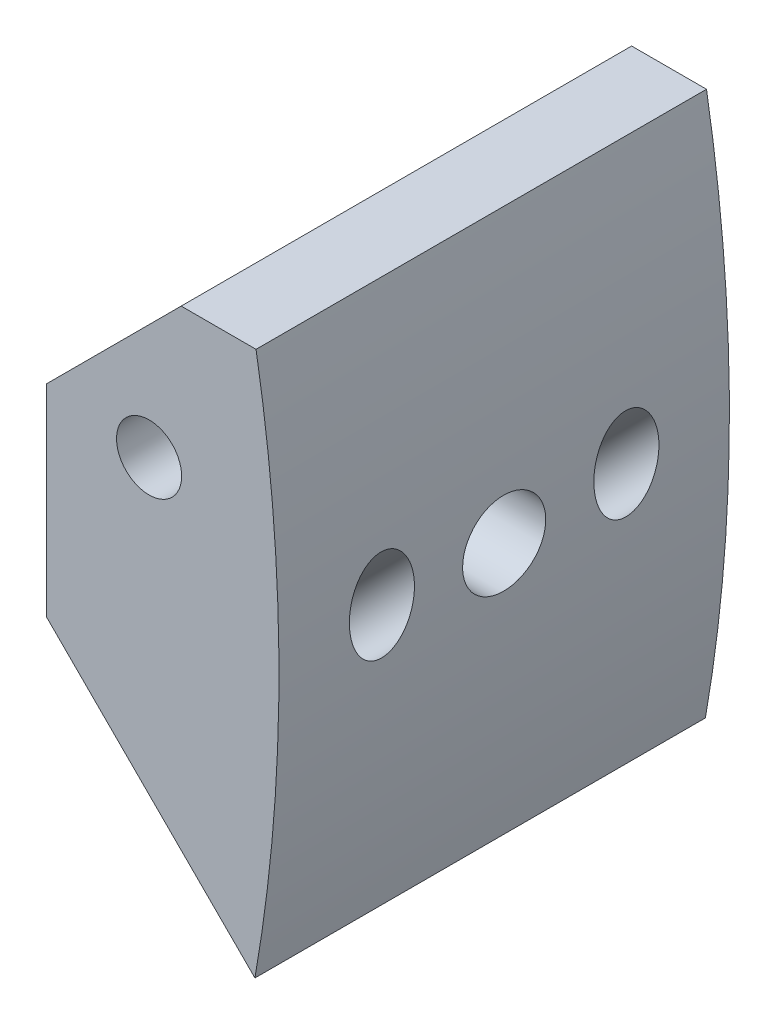
SolidWorks part; units mm, degrees
material "6061-T6 (SS)"
ref_plane "Front Plane" through (0, 0, 0) normal (0, 0, 1) x (1, 0, 0)
ref_plane "Top Plane" through (0, 0, 0) normal (0, 1, 0) x (1, 0, 0)
ref_plane "Right Plane" through (0, 0, 0) normal (1, 0, 0) x (0, 0, -1)
sketch "Sketch1" plane through (0, 0, 0) normal (0, 0, 1) x (1, 0, 0)
  line L0 (0, 0) -> (0, -13.1746)
  line L1 (0, -13.1746) -> (15.3242, -28.4988)
  line L2 (0, -6.5873) -> (15.3242, -6.5873) construction
  line L3 (15.3242, 15.3242) -> (0, 0) construction
  line L4 (15.3242, 15.3242) -> (15.3242, -6.5873) construction
  line L5 (15.3242, -6.5873) -> (15.3242, -28.4988) construction
  line L6 (19.05, -6.5873) -> (0, -6.5873) construction
  line L7 (0, 0) -> (0, 15.3242)
  line L8 (0, 15.3242) -> (15.3242, 15.3242)
  arc A0 (15.3242, 15.3242) -> (15.3242, -28.4988) centre (-47.244, -6.5873) cw
  dimension "D1" = 66.294
  dimension "D3" = 19.05
  dimension "D2" = 135
  dimension "D4" = 15.3242
extrude "Extrude1" add sketch "Sketch1" along normal blind 18.7198
sketch "Sketch23" plane through (0, 0, 0) normal (-1, 0, 0) x (0, 0, 1)
  line L0 (0, 0) -> (18.7198, 0) construction
  line L1 (18.7198, 15.3242) -> (18.7198, -13.1746) construction
  line L2 (9.3599, 0) -> (9.3599, -13.1746) construction
  line L3 (18.7198, -13.1746) -> (0, -13.1746) construction
  point P9 (9.3599, -6.5873)
sketch "Sketch2" plane through (0, 0, 0) normal (-1, 0, 0) x (0, 0, 1)
  line L0 (0, -6.5657) -> (18.7198, -6.5657) construction
  line L3 (9.3599, -13.1746) -> (9.3599, -6.5657) construction
  line L4 (18.7198, -13.1746) -> (0, -13.1746) construction
  point P6 (9.3599, -6.5657)
  dimension "D1" = 6.6089
sketch "Sketch13" plane through (0, 0, 18.7198) normal (0, 0, 1) x (1, 0, 0)
  line L0 (0, -13.1746) -> (0, 4.6054) construction
  line L1 (0, 4.6054) -> (30.3361, 4.6054)
  line L2 (0, 4.6054) -> (0, 31.0448)
  line L3 (0, 31.0448) -> (30.3361, 31.0448)
  line L4 (30.3361, 4.6054) -> (30.3361, 31.0448)
  dimension "D1" = 26.4394
  dimension "D2" = 30.3361
  dimension "D3" = 17.78
extrude "Extrude2" cut sketch "Sketch13" against normal through all
sketch "Sketch7" plane through (0, 0, 18.7198) normal (0, 0, 1) x (1, 0, 0)
  line L5 (19.05, -6.5873) -> (13.6525, -6.5873) construction
  line L6 (13.6525, -6.5873) -> (13.6525, -1.5073) construction
  arc A5 (15.3242, -28.4988) -> (18.0983, 4.6054) centre (-47.244, -6.5873) ccw construction
  dimension "D2" = 5.3975
  dimension "D4" = 5.08
hole_wizard "#6-32 Tapped Hole2" positions "Sketch9" profile "Sketch8" tap size "#6-32" standard "Ansi Inch" end condition through all
sketch "Sketch9" plane through (0, 0, 18.7198) normal (0, 0, 1) x (1, 0, 0)
  point P11 (13.6525, -1.5073)
sketch "Sketch8" plane through (13.6525, -1.5073, 18.7198) normal (1, 0, 0) x (0, -1, 0)
  line L0 (0, 0) -> (0, 18.7198)
  line L1 (0, 18.7198) -> (1.3525, 18.7198)
  line L2 (1.3525, 18.7198) -> (1.3525, 0)
  line L5 (1.3525, 0) -> (0, 0)
  line L11 (0, -6.35) -> (0, 107.95) construction
  dimension "Thread Major Dia." = 2.7051
  dimension "Thru Tap Drill Depth" = 18.7198
sketch "Sketch10" plane through (-6.5873, -6.5873, 0) normal (-0.7071, -0.7071, 0) x (0.7071, -0.7071, 0)
  line L0 (30.9875, 9.3599) -> (18.5415, 9.3599) construction
  line L2 (18.5415, 9.3599) -> (18.5415, 16.9799) construction
  line L3 (18.5415, 9.3599) -> (18.5415, 1.7399) construction
  line L5 (30.9875, 18.7198) -> (30.9875, 0) construction
  dimension "D1" = 7.62
  dimension "D2" = 12.446
sketch "Sketch14" plane through (0, 0, 18.7198) normal (0, 0, 1) x (1, 0, 0)
  line L0 (0.6847, -13.8593) -> (7.2762, -7.2678)
  line L1 (0, -13.1746) -> (15.3242, -28.4988) construction
  line L2 (7.2762, -7.2678) -> (18.0525, -18.0441)
  line L3 (21.9157, -21.9073) -> (15.3242, -28.4988)
  line L4 (15.3242, -28.4988) -> (0.6847, -13.8593)
  line L5 (18.0525, -18.0441) -> (21.9157, -21.9073)
  arc A0 (15.3242, -28.4988) -> (18.0983, 4.6054) centre (-47.244, -6.5873) ccw construction
  dimension "D2" = 9.3218
  dimension "D3" = 15.24
extrude "Extrude3" cut sketch "Sketch14" against normal through all
sketch "Sketch16" plane through (0.0042, 0.0042, 0) normal (-0.7071, -0.7071, 0) x (0, 0, 1)
  line L2 (9.3599, -17.8863) -> (14.4399, -17.8863) construction
  line L3 (9.3599, -17.8863) -> (4.2799, -17.8863) construction
  line L4 (9.3599, -25.5242) -> (9.3599, -17.8863) construction
  line L5 (18.7198, -25.5242) -> (0, -25.5242) construction
  dimension "D1" = 10.16
  dimension "D3" = 7.6379
hole_wizard "#6-32 Tapped Hole1" positions "3DSketch1" profile "Sketch17" tap size "#6-32" standard "Ansi Inch" end condition through all
sketch3d "3DSketch1"
  point P0 (12.6517, -12.6433, 14.4399)
  point P8 (12.6517, -12.6433, 4.2799)
sketch "Sketch17" plane through (12.6517, -12.6433, 14.4399) normal (0, 0, 1) x (0.7071, -0.7071, 0)
  line L0 (0, 0) -> (0, 16.7209)
  line L1 (0, 16.7209) -> (1.3525, 16.7209)
  line L2 (1.3525, 16.7209) -> (1.3525, 0)
  line L5 (1.3525, 0) -> (0, 0)
  line L11 (0, -6.35) -> (0, 107.95) construction
  dimension "Thread Major Dia." = 2.7051
  dimension "Thru Tap Drill Depth" = 16.7209
hole_wizard "#8-32 Tapped Hole1" positions "Sketch4" profile "Sketch5" tap size "#8-32" standard "Ansi Inch"
sketch "Sketch4" plane through (0, 0, 0) normal (-1, 0, 0) x (0, 0, 1)
  line L0 (0, -6.5657) -> (18.7198, -6.5657) construction
  point P1 (9.3599, -6.5657)
sketch "Sketch5" plane through (0, -6.5657, 9.3599) normal (0, 1, 0) x (0, 0, 1)
  line L0 (0, 0) -> (0, 19.05)
  line L1 (0, 19.05) -> (1.7272, 19.05)
  line L2 (1.7272, 19.05) -> (1.7272, 0)
  line L5 (1.7272, 0) -> (0, 0)
  line L11 (0, -6.35) -> (0, 107.95) construction
  dimension "Thread Major Dia." = 3.4544
  dimension "Thru Tap Drill Depth" = 19.05
hole_wizard "#8-32 Tapped Hole5" positions "Sketch26" profile "Sketch25" tap size "#8-32" standard "Ansi Inch"
sketch "Sketch26" plane through (0, 0, 0) normal (-1, 0, 0) x (0, 0, 1)
  point P1 (9.3599, -6.5873)
sketch "Sketch25" plane through (0, -6.5873, 9.3599) normal (0, 1, 0) x (0, 0, 1)
  line L0 (0, 0) -> (0, 20.0878)
  line L1 (0, 20.0878) -> (1.7272, 19.05)
  line L2 (1.7272, 19.05) -> (1.7272, 0)
  line L5 (1.7272, 0) -> (0, 0)
  line L10 (0, 20.0878) -> (-1.7272, 19.05) construction
  line L11 (0, -6.35) -> (0, 107.95) construction
  dimension "Tap Drill Dia." = 3.4544
  dimension "Tap Drill Depth" = 19.05
  dimension "Drill Angle" = 118
sketch "Sketch22" plane through (0, 0, 18.7198) normal (0, 0, 1) x (1, 0, 0)
  line L1 (0, 4.6054) -> (9.398, 4.6054)
  line L2 (0, 4.6054) -> (0, -17.0846)
  line L3 (0, -17.0846) -> (9.398, -17.0846)
  line L4 (9.398, 4.6054) -> (9.398, -17.0846)
  dimension "D1" = 21.6901
  dimension "D2" = 9.398
extrude "Extrude4" cut sketch "Sketch22" against normal through all
chamfer "Chamfer1" distance 5.588 angle 45 1 edges at (9.398, 4.6054, 9.3599)
